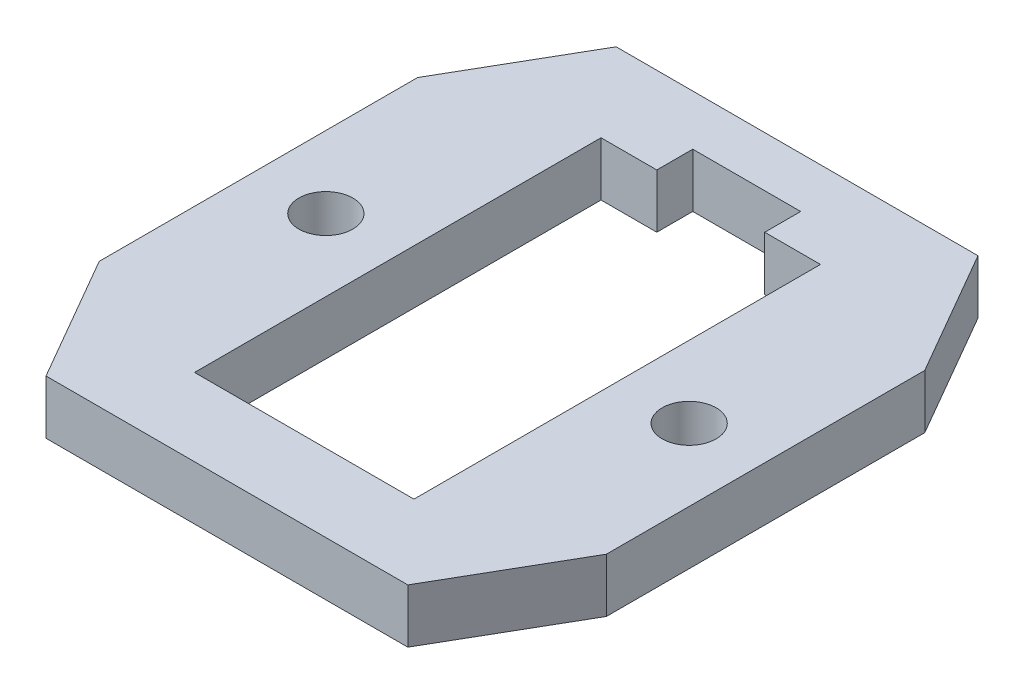
SolidWorks part; units mm, degrees
ref_plane "Front Plane" through (0, 0, 0) normal (0, 0, 1) x (1, 0, 0)
ref_plane "Top Plane" through (0, 0, 0) normal (0, 1, 0) x (1, 0, 0)
ref_plane "Right Plane" through (0, 0, 0) normal (1, 0, 0) x (0, 0, -1)
sketch "Sketch1" plane through (0, 0, 0) normal (0, 1, 0) x (1, 0, 0)
  line L0 (6.1, 0) -> (10.1, 0) construction
  line L5 (-6.1, -11.3) -> (6.1, -11.3)
  line L6 (-6.1, -11.3) -> (-6.1, 11.3)
  line L11 (-6.1, 11.3) -> (-3, 11.3)
  line L12 (6.1, -11.3) -> (6.1, 11.3)
  line L13 (-6.1, -11.3) -> (6.1, 11.3) construction
  line L14 (-6.1, 11.3) -> (6.1, -11.3) construction
  line L19 (-14.1, -16.1) -> (14.1, -16.1)
  line L20 (-14.1, -16.1) -> (-14.1, 16.1)
  line L21 (-14.1, 16.1) -> (14.1, 16.1)
  line L22 (14.1, -16.1) -> (14.1, 16.1)
  line L23 (-14.1, -16.1) -> (14.1, 16.1) construction
  line L24 (-14.1, 16.1) -> (14.1, -16.1) construction
  line L25 (0, 19.5933) -> (0, 13.3) construction
  line L26 (0, 0) -> (0, -20.4239) construction
  line L28 (-3, 11.3) -> (-3, 13.3)
  line L29 (-3, 13.3) -> (3, 13.3)
  line L30 (3, 11.3) -> (3, 13.3)
  line L33 (3, 11.3) -> (6.1, 11.3)
  line L34 (0, 11.3) -> (0, 9.3) construction
  circle A2 centre (10.1, 0) radius 1.5
  circle A3 centre (-10.1, 0) radius 1.5
  point P0 (0, 0)
  point P6 (0, 0)
  point P18 (0, 11.3)
  dimension "D6" = 3
  dimension "D1" = 22.6
  dimension "D2" = 12.2
  dimension "D3" = 4.8
  dimension "D4" = 8
  dimension "D5" = 4
  dimension "D7" = 6
extrude "Boss-Extrude1" add sketch "Sketch1" along normal blind 3
chamfer "Chamfer1" distance 7 angle 30 1 edges at (14.1, 1.5, -16.1)
chamfer "Chamfer3" distance 7 angle 30 1 edges at (-14.1, 1.5, -16.1)
sketch "Sketch2" plane through (0, 0, 16.1) normal (0, 0, 1) x (1, 0, 0)
  line L4 (-14.1, 0) -> (14.1, 0)
  line L5 (14.1, 0) -> (14.1, 3)
  line L6 (14.1, 3) -> (-14.1, 3)
  line L7 (-14.1, 3) -> (-14.1, 0)
  line L8 (-14.1, 0) -> (14.1, 0)
  line L9 (14.1, 0) -> (14.1, 3)
  line L10 (14.1, 3) -> (-14.1, 3)
  line L11 (-14.1, 3) -> (-14.1, 0)
  dimension "D1" = 0
extrude "Cut-Extrude1" cut sketch "Sketch2" against normal blind 0.5
chamfer "Chamfer4" distance 7 angle 30 1 edges at (-14.1, 1.5, 15.6)
chamfer "Chamfer5" distance 7 angle 30 1 edges at (14.1, 1.5, 15.6)
